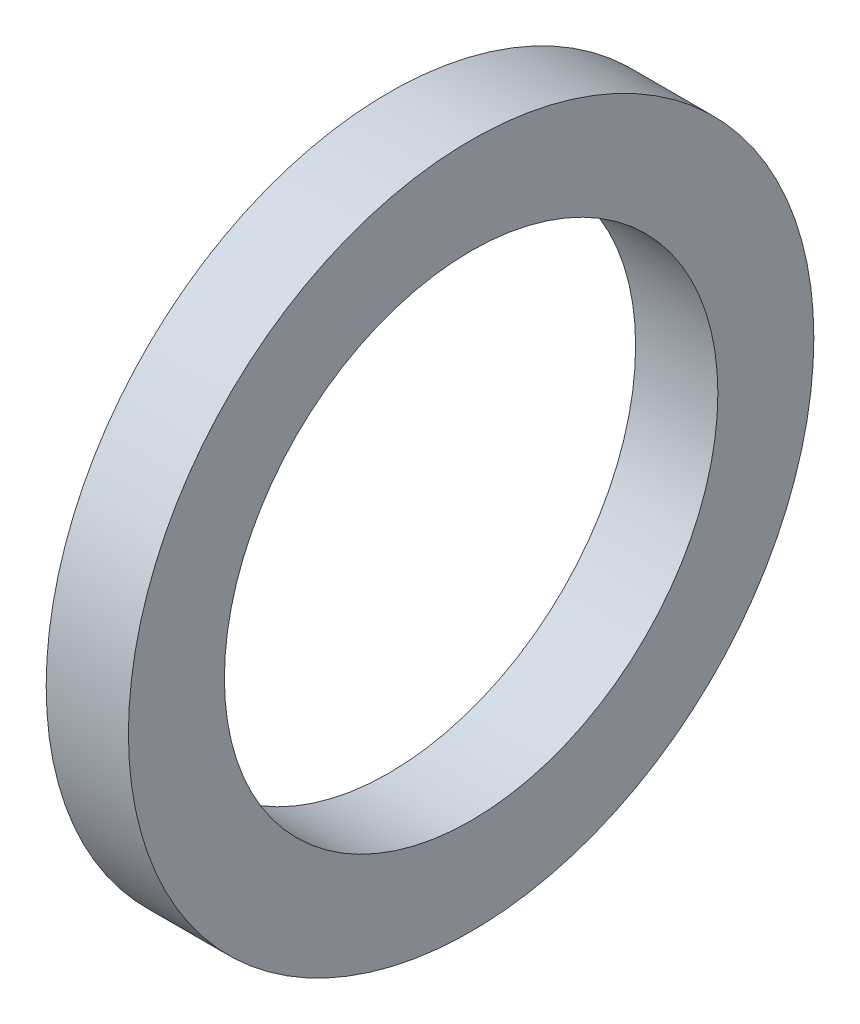
SolidWorks part; units mm, degrees
ref_plane "Plane1" through (0, 0, 0) normal (0, 0, 1) x (1, 0, 0)
ref_plane "Plane2" through (0, 0, 0) normal (0, 1, 0) x (1, 0, 0)
ref_plane "Plane3" through (0, 0, 0) normal (1, 0, 0) x (0, 0, -1)
sketch "Sketch1" plane through (0, 0, 0) normal (0, 0, 1) x (1, 0, 0)
  line L0 (-34.925, 0) -> (9.525, 0) construction
  line L1 (0, 18) -> (0, 25)
  line L2 (0, 25) -> (-6, 25)
  line L3 (-6, 25) -> (-6, 18)
  line L4 (-6, 18) -> (0, 18)
  dimension "Thickness" = 6
  dimension "Inside_dia" = 36
  dimension "Outside_dia" = 50
revolve "Base-Revolve" add sketch "Sketch1" angle 360 about L0
